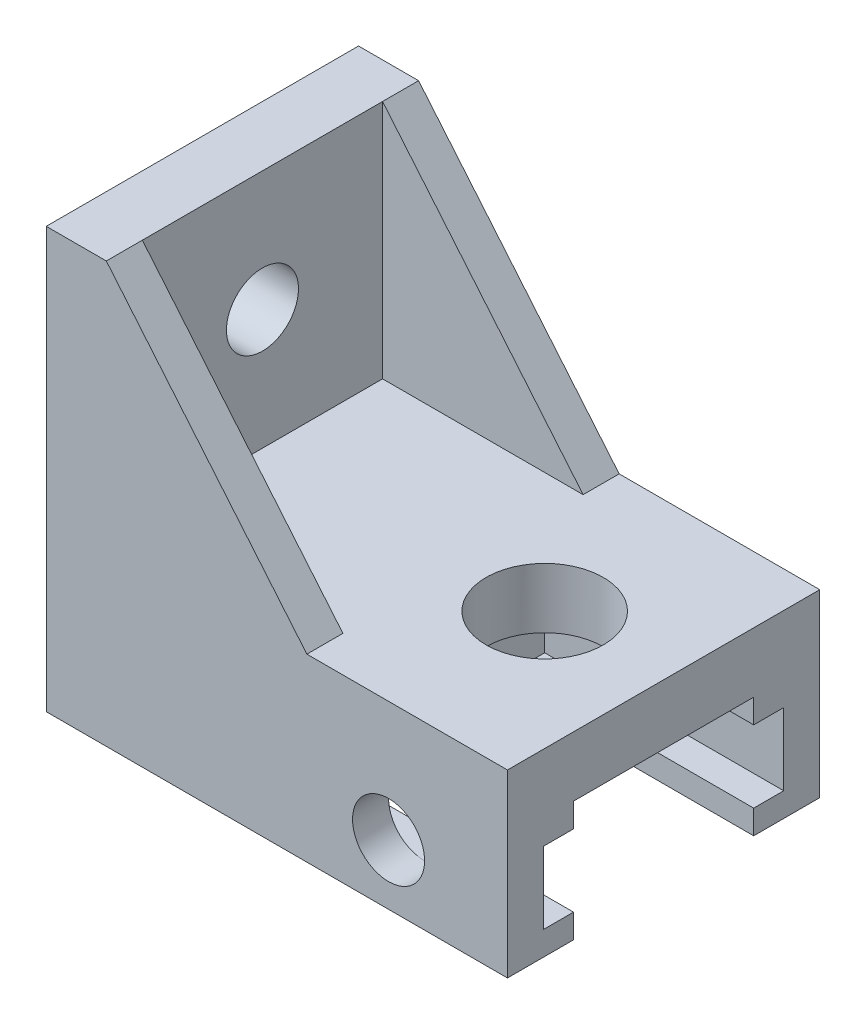
SolidWorks part; units mm, degrees
ref_plane "Front Plane" through (0, 0, 0) normal (0, 0, 1) x (1, 0, 0)
ref_plane "Top Plane" through (0, 0, 0) normal (0, 1, 0) x (1, 0, 0)
ref_plane "Right Plane" through (0, 0, 0) normal (1, 0, 0) x (0, 0, -1)
sketch "Sketch1" plane through (0, 0, 0) normal (0, 1, 0) x (1, 0, 0)
  line L1 (-13.5, 13) -> (13.5, 13)
  line L2 (-13.5, 13) -> (-13.5, -13)
  line L3 (-13.5, -13) -> (13.5, -13)
  line L4 (13.5, 13) -> (13.5, -13)
  line L5 (-13.5, 13) -> (13.5, -13) construction
  line L6 (-13.5, -13) -> (13.5, 13) construction
  point P0 (0, 0)
  dimension "D1" = 26
  dimension "D2" = 27
extrude "Boss-Extrude1" add sketch "Sketch1" along normal blind 15
sketch "Sketch4" plane through (13.5, 0, 0) normal (1, 0, 0) x (0, 0, -1)
  line L0 (-13, 15) -> (-13, 0) construction
  line L2 (-13, 7.5) -> (-13, 2.5)
  line L5 (-7.5, 2) -> (-7.5, 0)
  line L6 (-10, 8) -> (-7.5, 8)
  line L7 (-10, 8) -> (-10, 2)
  line L8 (-10, 2) -> (-7.5, 2)
  line L9 (10, 8) -> (10, 2)
  line L10 (-7.5, 10) -> (7.5, 10)
  line L11 (-7.5, 10) -> (-7.5, 8)
  line L12 (-7.5, 0) -> (7.5, 0)
  line L13 (7.5, 10) -> (7.5, 8)
  line L14 (7.5, 8) -> (10, 8)
  line L15 (7.5, 2) -> (10, 2)
  line L16 (7.5, 2) -> (7.5, 0)
  line M1 (-13, 0) -> (13, 0)
extrude "Cut-Extrude2" cut sketch "Sketch4" against normal blind 23.5 contours L16 L15 L9 L14 L13 L10 L11 L6 L7 L8 L5 M1
sketch "Sketch5" plane through (0, 0, -13) normal (0, 0, -1) x (-1, 0, 0)
  line L1 (-13.5, 15) -> (-9.8987, 15)
  line L2 (-13.5, 15) -> (-13.5, 0)
  line L3 (-13.5, 0) -> (-9.8987, 0)
  line L4 (-9.8987, 15) -> (-9.8987, 0)
extrude "Cut-Extrude3" cut sketch "Sketch5" against normal through all
sketch "Sketch6" plane through (0, 0, -13) normal (0, 0, -1) x (-1, 0, 0)
  circle A0 centre (0, 5) radius 3
  dimension "D1" = 6
extrude "Cut-Extrude4" cut sketch "Sketch6" against normal through all
sketch "Sketch11" plane through (0, 15, 0) normal (0, 1, 0) x (1, 0, 0)
  circle A0 centre (0, 0) radius 4.875
  dimension "D1" = 9.75
extrude "Cut-Extrude6" cut sketch "Sketch11" against normal through all
sketch "Sketch13" plane through (-13.5, 0, 0) normal (-1, 0, 0) x (0, 0, 1)
  line L1 (-13, 15) -> (13, 15)
  line L2 (-13, 15) -> (-13, 0)
  line L3 (-13, 0) -> (13, 0)
  line L4 (13, 15) -> (13, 0)
extrude "Boss-Extrude3" add sketch "Sketch13" along normal blind 15
sketch "Sketch14" plane through (0, 15, 0) normal (0, 1, 0) x (1, 0, 0)
  line L0 (-28.5, -13) -> (9.8987, -13) construction
  line L1 (-28.5, 13) -> (-23.5, 13)
  line L2 (-28.5, 13) -> (-28.5, -13)
  line L3 (-28.5, -13) -> (-23.5, -13)
  line L4 (-23.5, 13) -> (-23.5, -13)
  dimension "D1" = 5
extrude "Boss-Extrude4" add sketch "Sketch14" along normal blind 20
sketch "Sketch15" plane through (-23.5, 0, 0) normal (1, 0, 0) x (0, 0, -1)
  circle A0 centre (0, 25) radius 3
  dimension "D1" = 6
extrude "Cut-Extrude7" cut sketch "Sketch15" against normal blind 20
sketch "Sketch16" plane through (0, 0, -13) normal (0, 0, -1) x (-1, 0, 0)
  line L0 (23.5, 35) -> (6.8006, 15)
  line L1 (-9.8987, 15) -> (23.5, 15) construction
  line L2 (6.8006, 15) -> (23.5, 15)
  line L3 (23.5, 15) -> (23.5, 35)
extrude "Boss-Extrude5" add sketch "Sketch16" against normal blind 3
sketch "Sketch17" plane through (0, 0, 13) normal (0, 0, 1) x (1, 0, 0)
  line L0 (-23.5, 35) -> (-6.8006, 15)
  line L1 (-23.5, 15) -> (9.8987, 15) construction
  line L2 (-6.8006, 15) -> (-23.5, 15)
  line L3 (-23.5, 15) -> (-23.5, 35)
extrude "Boss-Extrude6" add sketch "Sketch17" against normal blind 3
